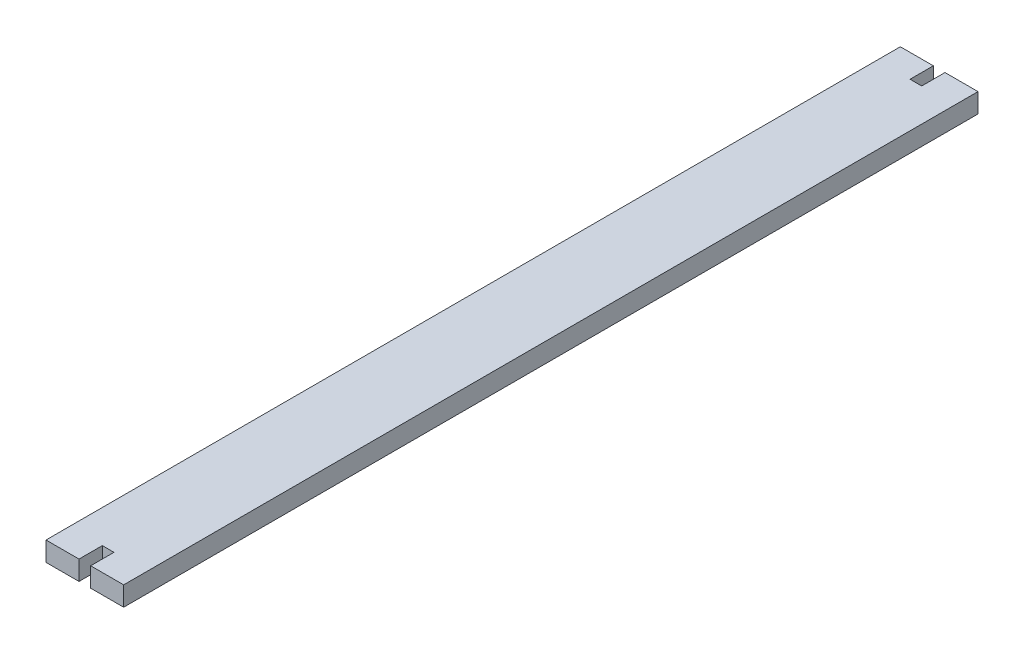
SolidWorks part; units mm, degrees
ref_plane "Front Plane" through (0, 0, 0) normal (0, 0, 1) x (1, 0, 0)
ref_plane "Top Plane" through (0, 0, 0) normal (0, 1, 0) x (1, 0, 0)
ref_plane "Right Plane" through (0, 0, 0) normal (1, 0, 0) x (0, 0, -1)
other "Configuration Table"
sketch "Sketch1" plane through (0, 0, 0) normal (0, 1, 0) x (1, 0, 0)
  line L1 (10, -110) -> (-10, -110)
  line L2 (10, -110) -> (10, 110)
  line L3 (10, 110) -> (-10, 110)
  line L4 (-10, -110) -> (-10, 110)
  line L5 (10, -110) -> (-10, 110) construction
  line L6 (10, 110) -> (-10, -110) construction
  point P0 (0, 0)
  dimension "D1" = 20
  dimension "D2" = 220
extrude "Boss-Extrude1" add sketch "Sketch1" against normal blind 5
sketch "Sketch2" plane through (0, 0, 0) normal (0, 1, 0) x (1, 0, 0)
  line L14 (1.5, -104) -> (-1.5, -104)
  line L22 (0, -110) -> (0, 110) construction
  line L23 (-10, -110) -> (10, -110) construction
  line L24 (10, 110) -> (-10, 110) construction
  line L25 (1.5, -104) -> (1.5, -110)
  line L26 (1.5, 104) -> (-1.5, 104)
  line L27 (1.5, 104) -> (1.5, 110)
  line L28 (1.5, 110) -> (-1.5, 110)
  line L29 (-1.5, 104) -> (-1.5, 110)
  line L30 (1.5, 104) -> (-1.5, 110) construction
  line L31 (1.5, 110) -> (-1.5, 104) construction
  line L32 (1.5, -110) -> (-1.5, -110)
  line L33 (-1.5, -104) -> (-1.5, -110)
  line L34 (1.5, -104) -> (-1.5, -110) construction
  line L35 (1.5, -110) -> (-1.5, -104) construction
  point P6 (0, 107)
  point P11 (0, -107)
  dimension "D1" = 6
  dimension "D2" = 3
  dimension "D3" = 6
extrude "Cut-Extrude1" cut sketch "Sketch2" against normal through all
